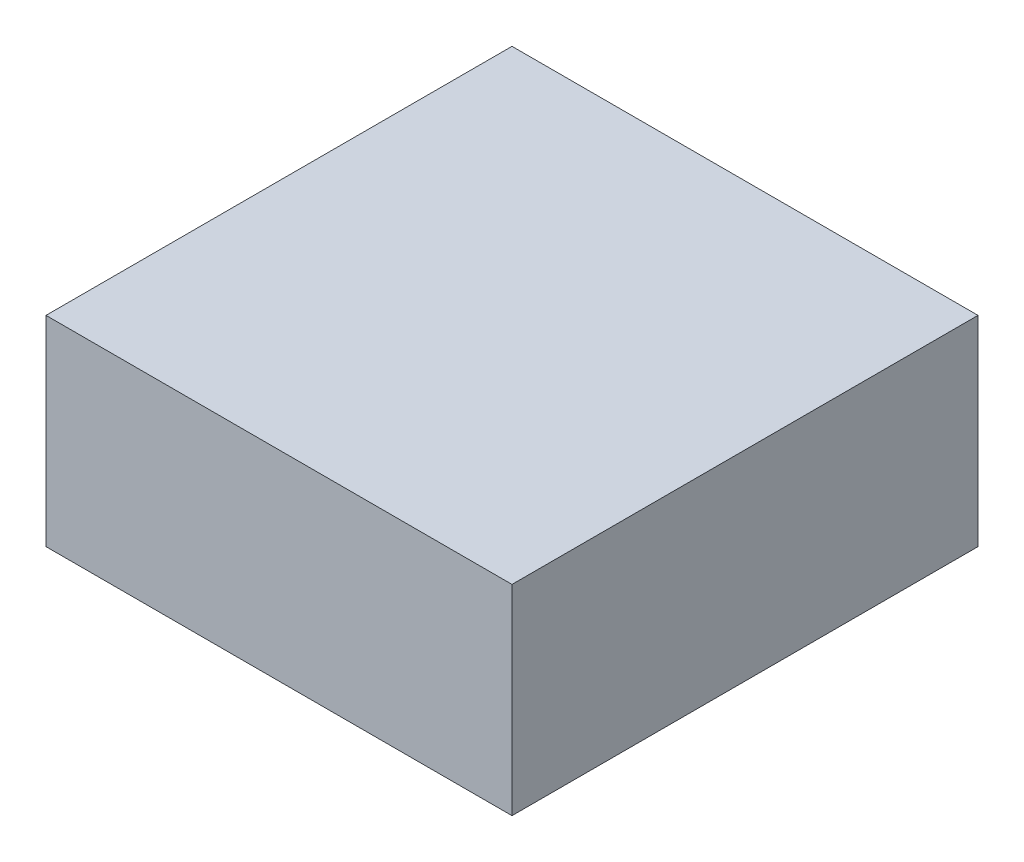
SolidWorks part; units mm, degrees
ref_plane "Front Plane" through (0, 0, 0) normal (0, 0, 1) x (1, 0, 0)
ref_plane "Top Plane" through (0, 0, 0) normal (0, 1, 0) x (1, 0, 0)
ref_plane "Right Plane" through (0, 0, 0) normal (1, 0, 0) x (0, 0, -1)
sketch "Sketch1" plane through (0, 0, 0) normal (0, 1, 0) x (1, 0, 0)
  line L1 (0, 0) -> (57.912, 0)
  line L2 (0, 0) -> (0, 57.912)
  line L3 (0, 57.912) -> (57.912, 57.912)
  line L4 (57.912, 0) -> (57.912, 57.912)
  dimension "D1" = 57.912
  dimension "D2" = 57.912
extrude "Boss-Extrude1" add sketch "Sketch1" along normal blind 24.892
